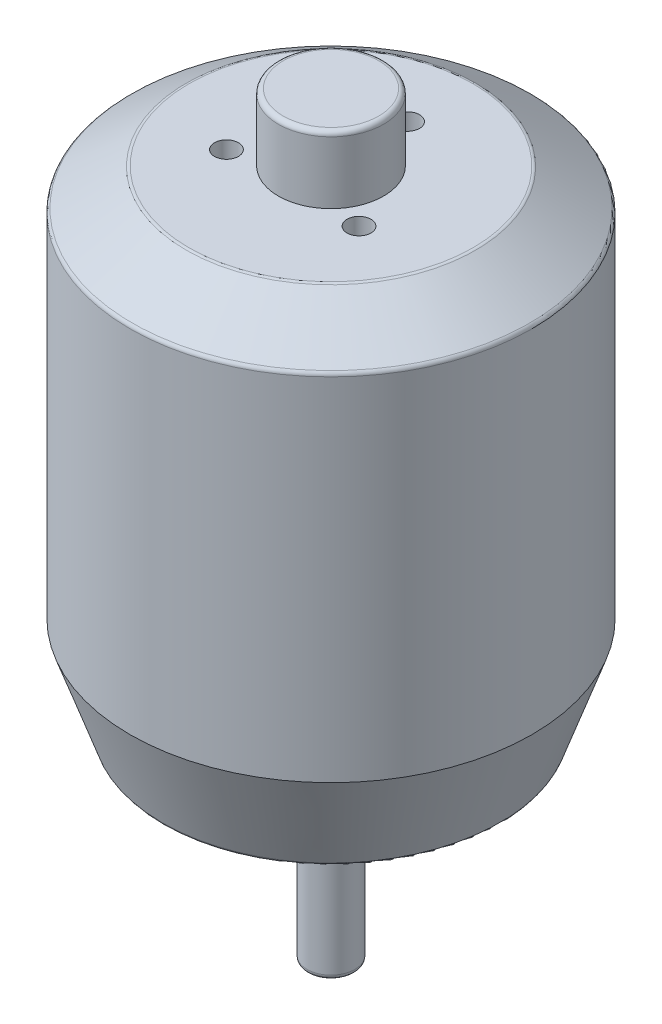
SolidWorks part; units mm, degrees
material "Cast Alloy Steel"
ref_plane "Front" through (0, 0, 0) normal (0, 0, 1) x (1, 0, 0)
ref_plane "Top" through (0, 0, 0) normal (0, 1, 0) x (1, 0, 0)
ref_plane "Right" through (0, 0, 0) normal (1, 0, 0) x (0, 0, -1)
sketch "Sketch1" plane through (0, 0, 0) normal (0, 1, 0) x (1, 0, 0)
  circle A0 centre (0, 0) radius 17.5
  dimension "D1" = 35
extrude "Boss-Extrude1" add sketch "Sketch1" along normal blind 10 contours A0
sketch "Sketch2" plane through (0, 10, 0) normal (0, 1, 0) x (1, 0, 0)
  circle A0 centre (0, 0) radius 21
  dimension "D1" = 42
extrude "Boss-Extrude2" add sketch "Sketch2" along normal blind 37
sketch "Sketch3" plane through (0, 47, 0) normal (0, 1, 0) x (1, 0, 0)
  circle A0 centre (0, 0) radius 15
  dimension "D1" = 30
extrude "Boss-Extrude3" add sketch "Sketch3" along normal blind 4
sketch "Sketch4" plane through (0, 51, 0) normal (0, 1, 0) x (1, 0, 0)
  circle A0 centre (0, 0) radius 5.5
  dimension "D1" = 11
extrude "Boss-Extrude4" add sketch "Sketch4" along normal blind 7
sketch "Sketch5" plane through (0, 0, 0) normal (0, -1, 0) x (1, 0, 0)
  circle A0 centre (0, 0) radius 2.5
  dimension "D1" = 5
extrude "Boss-Extrude5" add sketch "Sketch5" along normal blind 21
loft "Loft1" add section edge at (0, 0, 17.5) section edge at (0, 10, 21)
loft "Loft2" add section edge at (0, 51, 15) section edge at (0, 47, 21)
sketch "Sketch6" plane through (0, 0, 0) normal (0, -1, 0) x (1, 0, 0)
  line L0 (0, 0) -> (-16.3695, 16.3695) construction
  circle A0 centre (0, 12.5) radius 1.5
  circle A1 centre (12.5, 0) radius 1.5
  circle A2 centre (0, -12.5) radius 1.5
  circle A3 centre (-12.5, 0) radius 1.5
  circle A4 centre (-8.8388, 8.8388) radius 4
  circle A5 centre (8.8388, 8.8388) radius 4
  circle A6 centre (8.8388, -8.8388) radius 4
  circle A7 centre (-8.8388, -8.8388) radius 4
  point P12 (0, 0)
  point P24 (0, 0)
  dimension "D1" = 3
  dimension "D5" = 8
  dimension "D2" = 12.5
  dimension "D4" = 12.5
  dimension "D3" = 4
  dimension "D6" = 4
extrude "Cut-Extrude1" cut sketch "Sketch6" against normal blind 10
sketch "Sketch7" plane through (0, 0, 0) normal (0, -1, 0) x (1, 0, 0)
  circle A0 centre (0, 0) radius 5.5
  dimension "D1" = 11
extrude "Boss-Extrude6" add sketch "Sketch7" along normal blind 1
sketch "Sketch9" plane through (0, 51, 0) normal (0, 1, 0) x (1, 0, 0)
  circle A0 centre (0, 8) radius 1.25
  circle A1 centre (6.9282, -4) radius 1.25
  circle A2 centre (-6.9282, -4) radius 1.25
  point P9 (0, 0)
  dimension "D1" = 2.5
  dimension "D2" = 8
  dimension "D3" = 3
extrude "Cut-Extrude2" cut sketch "Sketch9" against normal blind 10
sketch "Sketch10" plane through (0, 0, 0) normal (0, -1, 0) x (1, 0, 0)
  line L0 (-24, 6) -> (-12, 6)
  line L5 (-30, 30) -> (30, -30) construction
  line L6 (-30, -30) -> (30, 30) construction
  line L7 (-6, 12) -> (-6, 24)
  line L8 (6, 24) -> (6, 12)
  line L9 (12, 6) -> (24, 6)
  line L10 (24, -6) -> (12, -6)
  line L11 (6, -12) -> (6, -24)
  line L12 (-6, -24) -> (-6, -12)
  line L13 (-12, -6) -> (-24, -6)
  circle A0 centre (0, 12.5) radius 1.5
  arc A1 (-30, 0) -> (-24, 6) centre (-24, 0) cw
  arc A2 (-12, 6) -> (-6, 12) centre (-12, 12) ccw
  arc A3 (0, 30) -> (-6, 24) centre (0, 24) ccw
  arc A4 (0, 30) -> (6, 24) centre (0, 24) cw
  arc A5 (6, 12) -> (12, 6) centre (12, 12) ccw
  arc A6 (30, 0) -> (24, 6) centre (24, 0) ccw
  arc A7 (30, 0) -> (24, -6) centre (24, 0) cw
  arc A8 (12, -6) -> (6, -12) centre (12, -12) ccw
  arc A9 (0, -30) -> (6, -24) centre (0, -24) ccw
  arc A10 (0, -30) -> (-6, -24) centre (0, -24) cw
  arc A11 (-6, -12) -> (-12, -6) centre (-12, -12) ccw
  arc A12 (-30, 0) -> (-24, -6) centre (-24, 0) ccw
  circle A13 centre (-12.5, 0) radius 1.5
  circle A14 centre (-25, 0) radius 1.5
  circle A15 centre (0, 25) radius 1.5
  circle A16 centre (12.5, 0) radius 1.5
  circle A17 centre (25, 0) radius 1.5
  circle A18 centre (0, -12.5) radius 1.5
  circle A19 centre (0, -25) radius 1.5
  point P0 (0, 0)
  point P13 (-6, 6)
  point P46 (0, 0)
  point P60 (0, 0)
  dimension "D1" = 6
  dimension "D2" = 6
  dimension "D3" = 6
  dimension "D5" = 25
  dimension "D6" = 3
  dimension "D4" = 4
  dimension "D7" = 4
extrude "Boss-Extrude7" [suppressed] add sketch "Sketch10" along normal blind 3
chamfer "Chamfer1" [suppressed] distance 1.5 angle 60
fillet "Fillet1" radius 0.5 5 edges at (0, -21, -2.5) (0, 0, 17.5) (0, 47, 21) (0, 51, 15) (0, 58, 5.5)
